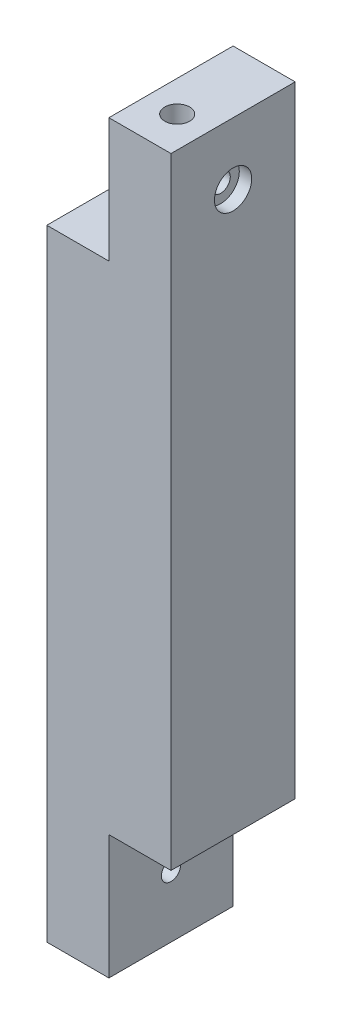
SolidWorks part; units mm, degrees
ref_plane "前视基准面" through (0, 0, 0) normal (0, 0, 1) x (1, 0, 0)
ref_plane "上视基准面" through (0, 0, 0) normal (0, 1, 0) x (1, 0, 0)
ref_plane "右视基准面" through (0, 0, 0) normal (1, 0, 0) x (0, 0, -1)
other "Configuration Table"
sketch "草图1" plane through (0, 0, 0) normal (0, 1, 0) x (1, 0, 0)
  line L1 (-17.9813, 3.5461) -> (2.0187, 3.5461)
  line L2 (-17.9813, 3.5461) -> (-17.9813, -16.4539)
  line L3 (-17.9813, -16.4539) -> (2.0187, -16.4539)
  line L4 (2.0187, 3.5461) -> (2.0187, -16.4539)
extrude "凸台-拉伸1" add sketch "草图1" along normal blind 120 contours L2 L1 L4 L3
sketch "草图2" plane through (0, 0, 16.4539) normal (0, 0, 1) x (1, 0, 0)
  line L1 (-17.9813, 120) -> (-7.9813, 120)
  line L2 (-17.9813, 120) -> (-17.9813, 100)
  line L3 (-17.9813, 100) -> (-7.9813, 100)
  line L4 (-7.9813, 120) -> (-7.9813, 100)
extrude "切除-拉伸1" cut sketch "草图2" against normal blind 120 contours L2 L1 L4 L3
sketch "草图3" plane through (0, 0, 16.4539) normal (0, 0, 1) x (1, 0, 0)
  line L1 (2.0187, 0) -> (-7.9813, 0)
  line L2 (2.0187, 0) -> (2.0187, 20)
  line L3 (2.0187, 20) -> (-7.9813, 20)
  line L4 (-7.9813, 0) -> (-7.9813, 20)
extrude "切除-拉伸2" cut sketch "草图3" against normal blind 120 contours L2 L1 L4 L3
sketch "草图4" plane through (-7.9813, 0, 0) normal (-1, 0, 0) x (0, 0, 1)
  line L0 (-3.5461, 120) -> (16.4539, 100)
  circle A0 centre (6.4539, 110) radius 1.55
extrude "切除-拉伸3" cut sketch "草图4" against normal blind 120 contours L0 A0 | L0 A0
sketch "草图5" plane through (2.0187, 0, 0) normal (1, 0, 0) x (0, 0, -1)
  circle A0 centre (-6.4539, 110) radius 3
extrude "切除-拉伸4" cut sketch "草图5" against normal blind 2
sketch "草图6" plane through (-7.9813, 0, 0) normal (1, 0, 0) x (0, 0, -1)
  line L0 (-16.4539, 20) -> (3.5461, 0)
  circle A0 centre (-6.4539, 10) radius 1.55
extrude "切除-拉伸5" cut sketch "草图6" against normal blind 20 contours L0 A0 | L0 A0
sketch "草图7" plane through (-17.9813, 0, 0) normal (-1, 0, 0) x (0, 0, 1)
  circle A0 centre (6.4539, 10) radius 3
extrude "切除-拉伸6" cut sketch "草图7" against normal blind 2
sketch "草图8" plane through (0, 20, 0) normal (0, -1, 0) x (1, 0, 0)
  line L0 (-7.9813, 16.4539) -> (2.0187, -3.5461)
  line L1 (-2.9813, 6.4539) -> (-2.9813, 10.4539)
  circle A0 centre (-2.9813, 10.4539) radius 2
extrude "切除-拉伸7" cut sketch "草图8" against normal blind 100
